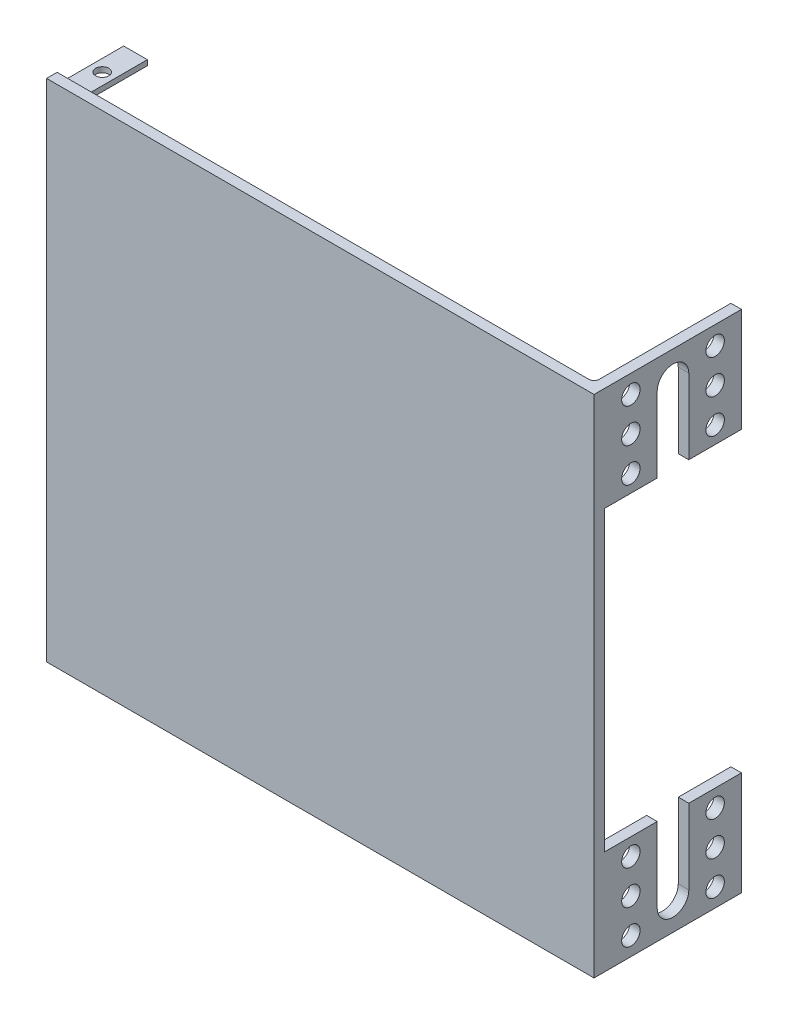
SolidWorks part; units mm, degrees
ref_plane "前视基准面" through (0, 0, 0) normal (0, 0, 1) x (1, 0, 0)
ref_plane "上视基准面" through (0, 0, 0) normal (0, 1, 0) x (1, 0, 0)
ref_plane "右视基准面" through (0, 0, 0) normal (1, 0, 0) x (0, 0, -1)
other "Configuration Table"
sketch "草图1" plane through (0, 0, 0) normal (0, 0, 1) x (1, 0, 0)
  line L1 (-52, -48) -> (52, -48)
  line L2 (-52, -48) -> (-52, 48)
  line L3 (-52, 48) -> (52, 48)
  line L4 (52, -48) -> (52, 48)
  line L5 (-52, -48) -> (52, 48) construction
  line L6 (-52, 48) -> (52, -48) construction
  point P0 (0, 0)
  dimension "D1" = 104
  dimension "D2" = 96
extrude "凸台-拉伸1" add sketch "草图1" along normal blind 2
sketch "草图2" plane through (0, 0, 0) normal (0, 0, -1) x (-1, 0, 0)
  line L0 (-52, 48) -> (52, 48) construction
  line L1 (-52, -48) -> (-50, -48)
  line L2 (-52, -48) -> (-52, 48)
  line L3 (-52, 48) -> (-50, 48)
  line L4 (-50, -48) -> (-50, 48)
  dimension "D1" = 2
extrude "凸台-拉伸2" add sketch "草图2" along normal blind 26
sketch "草图3" plane through (50, 0, 0) normal (-1, 0, 0) x (0, 0, 1)
  line L0 (-13, 48) -> (-13, -48) construction
  line L1 (-26, 48) -> (0, 48) construction
  line L2 (-26, -48) -> (0, -48) construction
  line L3 (2, 48) -> (2, -48) construction
  line L4 (-13, 0) -> (0, 0) construction
  circle A0 centre (-5, 44.5) radius 1.75
  circle A1 centre (-5, 38) radius 1.75
  circle A2 centre (-5, 31.5) radius 1.75
  circle A5 centre (-21, 31.5) radius 1.75
  circle A6 centre (-21, 38) radius 1.75
  circle A7 centre (-21, 44.5) radius 1.75
  circle A8 centre (-21, -44.5) radius 1.75
  circle A9 centre (-21, -38) radius 1.75
  circle A10 centre (-21, -31.5) radius 1.75
  circle A11 centre (-5, -31.5) radius 1.75
  circle A12 centre (-5, -38) radius 1.75
  circle A13 centre (-5, -44.5) radius 1.75
  dimension "D1" = 3.5
  dimension "D2" = 7
  dimension "D5" = 6.5
  dimension "D3" = 3.5
  dimension "D4" = 3
extrude "切除-拉伸1" cut sketch "草图3" against normal through all
sketch "草图4" plane through (52, 0, 0) normal (1, 0, 0) x (0, 0, -1)
  line L0 (26, 48) -> (26, -48) construction
  line L1 (0, -28.25) -> (26, -28.25)
  line L2 (0, -28.25) -> (0, 28.25)
  line L3 (0, 28.25) -> (26, 28.25)
  line L4 (26, -28.25) -> (26, 28.25)
  line L5 (0, -28.25) -> (26, 28.25) construction
  line L6 (0, 28.25) -> (26, -28.25) construction
  line L7 (-2, -48) -> (-2, 48) construction
  line L8 (0, 0) -> (13, 0) construction
  circle A0 centre (21, 31.5) radius 1.75 construction
  point P0 (13, 0)
  point P9 (26, 26.6884)
  dimension "D2" = 3.25
  dimension "D1" = 2
extrude "切除-拉伸2" cut sketch "草图4" against normal through all
fillet "圆角2" radius 1 2 edges at (50, 38.125, 0) (50, -38.125, 0)
sketch "草图5" plane through (52, 0, 0) normal (1, 0, 0) x (0, 0, -1)
  line L0 (26, 28.25) -> (0, 28.25) construction
  line L1 (10, 28.25) -> (16, 28.25)
  line L2 (10, 28.25) -> (10, 42.5)
  line L3 (10, 42.5) -> (16, 42.5)
  line L4 (16, 28.25) -> (16, 42.5)
  line L5 (13, 28.25) -> (13, 48) construction
  line L6 (-2, 48) -> (26, 48) construction
  line L7 (0, 0) -> (-2, 0) construction
  line L8 (-2, -48) -> (-2, 48) construction
  line L9 (13, -28.25) -> (13, -48) construction
  line L10 (16, -28.25) -> (16, -42.5)
  line L11 (10, -42.5) -> (16, -42.5)
  line L12 (10, -28.25) -> (10, -42.5)
  line L13 (10, -28.25) -> (16, -28.25)
  arc A0 (10, 42.5) -> (16, 42.5) centre (13, 42.5) cw
  arc A1 (10, -42.5) -> (16, -42.5) centre (13, -42.5) ccw
  line M18 (26, -28.25) -> (0, -28.25)
  line M20 (0, 28.25) -> (26, 28.25)
  dimension "D1" = 14.25
  dimension "D2" = 6
extrude "切除-拉伸3" cut sketch "草图5" against normal through all contours L4 L3 L2 M20 | A0 L3 | L12 L11 L10 M18 | L11 A1
sketch "草图6" plane through (0, 0, 0) normal (0, 0, -1) x (-1, 0, 0)
  line L6 (52, 48) -> (52, -48) construction
  line L7 (52, 46) -> (47.5, 46)
  line L8 (52, 46) -> (52, 45)
  line L9 (52, 45) -> (47.5, 45)
  line L10 (47.5, 46) -> (47.5, 45)
  line L11 (-49, 48) -> (52, 48) construction
  dimension "D1" = 2
  dimension "D2" = 1
  dimension "D3" = 4.5
extrude "凸台-拉伸3" add sketch "草图6" along normal blind 12.65
sketch "草图7" plane through (0, 46, 0) normal (0, 1, 0) x (1, 0, 0)
  line L0 (-52, 12.65) -> (-47.5, 0) construction
  circle A0 centre (-49.75, 6.325) radius 1.25
  point P6 (-49.75, 6.325)
  dimension "D1" = 2.5
extrude "切除-拉伸4" cut sketch "草图7" against normal through all
mirror "镜向1" about plane through (0, 0, 0) normal (0, 1, 0) of "切除-拉伸4", "凸台-拉伸3"
